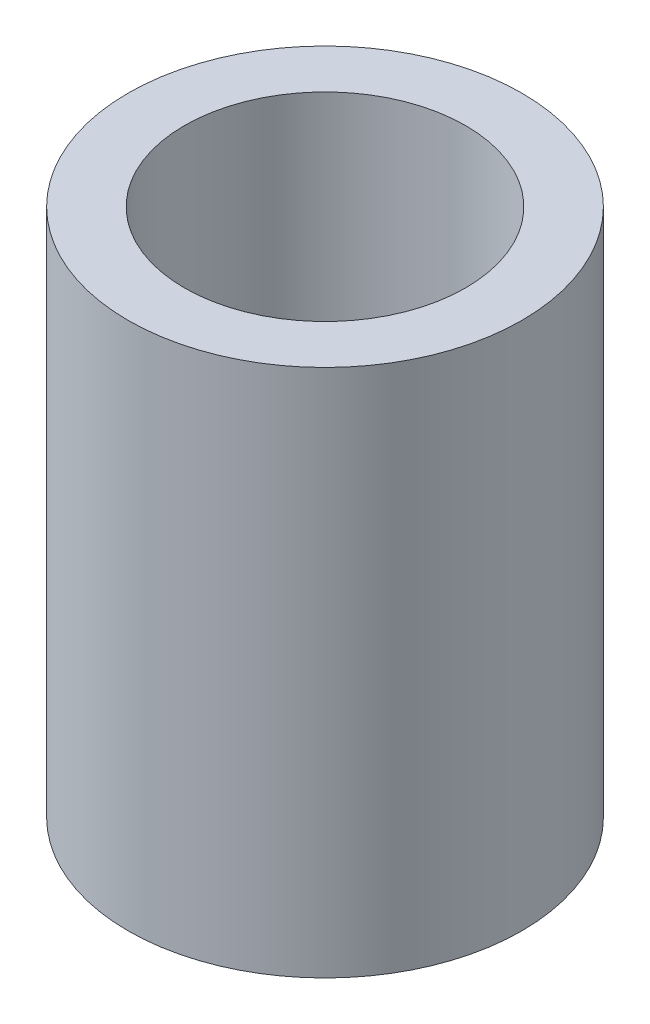
SolidWorks part; units mm, degrees
ref_plane "Piano frontale" through (0, 0, 0) normal (0, 0, 1) x (1, 0, 0)
ref_plane "Piano superiore" through (0, 0, 0) normal (0, 1, 0) x (1, 0, 0)
ref_plane "Piano destro" through (0, 0, 0) normal (1, 0, 0) x (0, 0, -1)
sketch "Schizzo1" plane through (0, 0, 0) normal (0, 1, 0) x (1, 0, 0)
  circle A0 centre (0, 0) radius 2.5
  dimension "D1" = 5
extrude "Estrusione-Sottile1" add sketch "Schizzo1" along normal blind 9.4 thin
